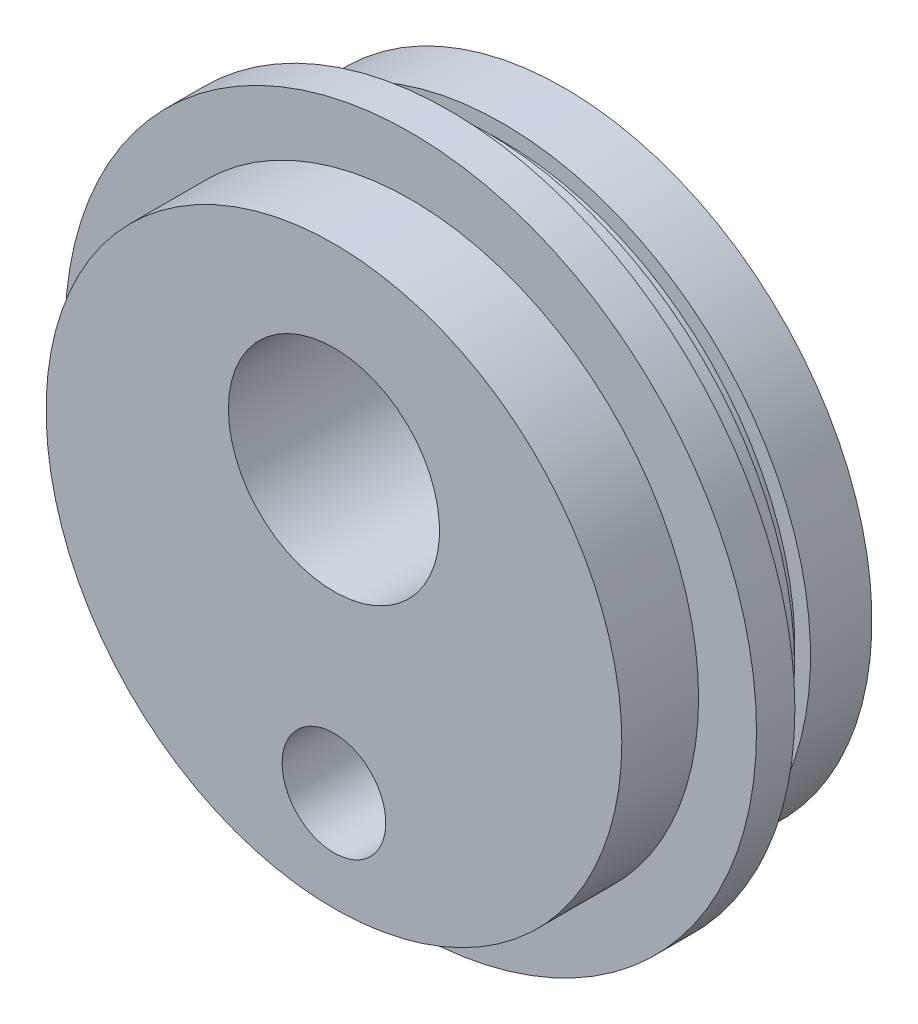
SolidWorks part; units mm, degrees
ref_plane "Front Plane" through (0, 0, 0) normal (0, 0, 1) x (1, 0, 0)
ref_plane "Top Plane" through (0, 0, 0) normal (0, 1, 0) x (1, 0, 0)
ref_plane "Right Plane" through (0, 0, 0) normal (1, 0, 0) x (0, 0, -1)
sketch "Sketch1" plane through (0, 0, 0) normal (0, 0, 1) x (1, 0, 0)
  circle A0 centre (0, 0) radius 50.8
  dimension "D1" = 101.6
extrude "Boss-Extrude1" add sketch "Sketch1" along normal blind 25.4
sketch "Sketch23" plane through (0, 0, 25.4) normal (0, 0, 1) x (1, 0, 0)
  circle A0 centre (0, 0) radius 47.625
  dimension "D1" = 95.25
extrude "Cut-Extrude-Thin2" cut sketch "Sketch23" against normal blind 12.7 thin
sketch "Sketch26" plane through (0, 0, 12.7) normal (0, 0, 1) x (1, 0, 0)
  circle A0 centre (0, 0) radius 57.2064
extrude "Boss-Extrude3" add sketch "Sketch26" against normal blind 6.35
sketch "Sketch31" plane through (0, 0, 0) normal (0, 0, -1) x (-1, 0, 0)
  circle A0 centre (0, 0) radius 48.308
extrude "Boss-Extrude4" add sketch "Sketch31" along normal blind 2.54
sketch "Sketch32" plane through (0, 0, -2.54) normal (0, 0, -1) x (-1, 0, 0)
  circle A0 centre (0, 0) radius 50.9006
extrude "Boss-Extrude5" add sketch "Sketch32" along normal blind 10.16
sketch "Sketch20" plane through (0, 0, 0) normal (0, 0, -1) x (-1, 0, 0)
  circle A0 centre (0, 15.24) radius 17.4625
  dimension "D1" = 34.925
extrude "Cut-Extrude5" cut sketch "Sketch20" against normal through all both and the other way through all
sketch "Sketch21" plane through (0, 0, 0) normal (0, 0, -1) x (-1, 0, 0)
  circle A0 centre (0, -31.0865) radius 8.5725
  dimension "D1" = 17.145
extrude "Cut-Extrude6" cut sketch "Sketch21" against normal through all both and the other way through all
